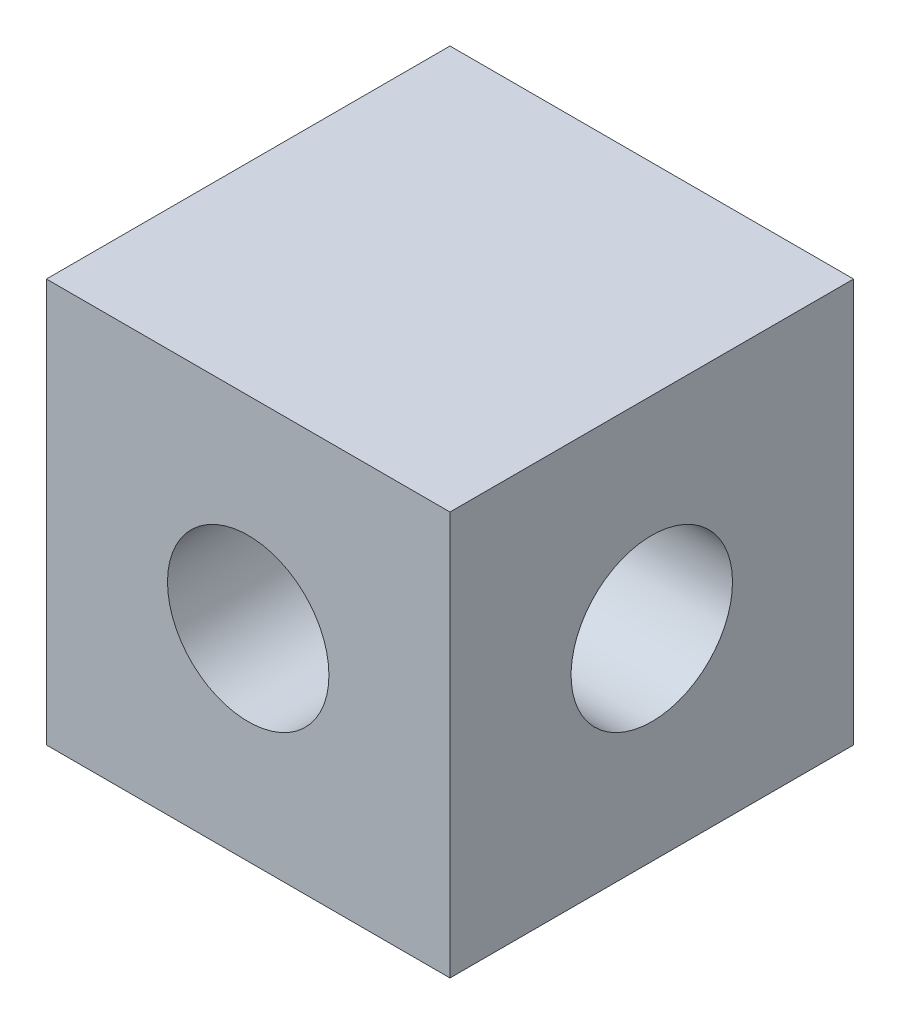
SolidWorks part; units mm, degrees
ref_plane "前视基准面" through (0, 0, 0) normal (0, 0, 1) x (1, 0, 0)
ref_plane "上视基准面" through (0, 0, 0) normal (0, 1, 0) x (1, 0, 0)
ref_plane "右视基准面" through (0, 0, 0) normal (1, 0, 0) x (0, 0, -1)
sketch "草图1" plane through (0, 0, 0) normal (1, 0, 0) x (0, 0, -1)
  line L5 (-5, -5) -> (5, -5)
  line L6 (-5, -5) -> (-5, 5)
  line L7 (-5, 5) -> (5, 5)
  line L8 (5, -5) -> (5, 5)
  line L9 (-5, -5) -> (5, 5) construction
  line L10 (-5, 5) -> (5, -5) construction
  circle A0 centre (0, 0) radius 2
  point P0 (0, 0)
  point P6 (0, 0)
  dimension "D2" = 4
  dimension "D1" = 10
extrude "凸台-拉伸1" add sketch "草图1" along normal blind 10
sketch "草图2" plane through (0, 0, -5) normal (0, 0, -1) x (-1, 0, 0)
  line L0 (-10, 5) -> (0, -5) construction
  line L1 (0, 5) -> (-10, -5) construction
  circle A0 centre (-5, 0) radius 2
  point P10 (-5, 0)
  dimension "D1" = 4
extrude "切除-拉伸1" cut sketch "草图2" against normal through all
